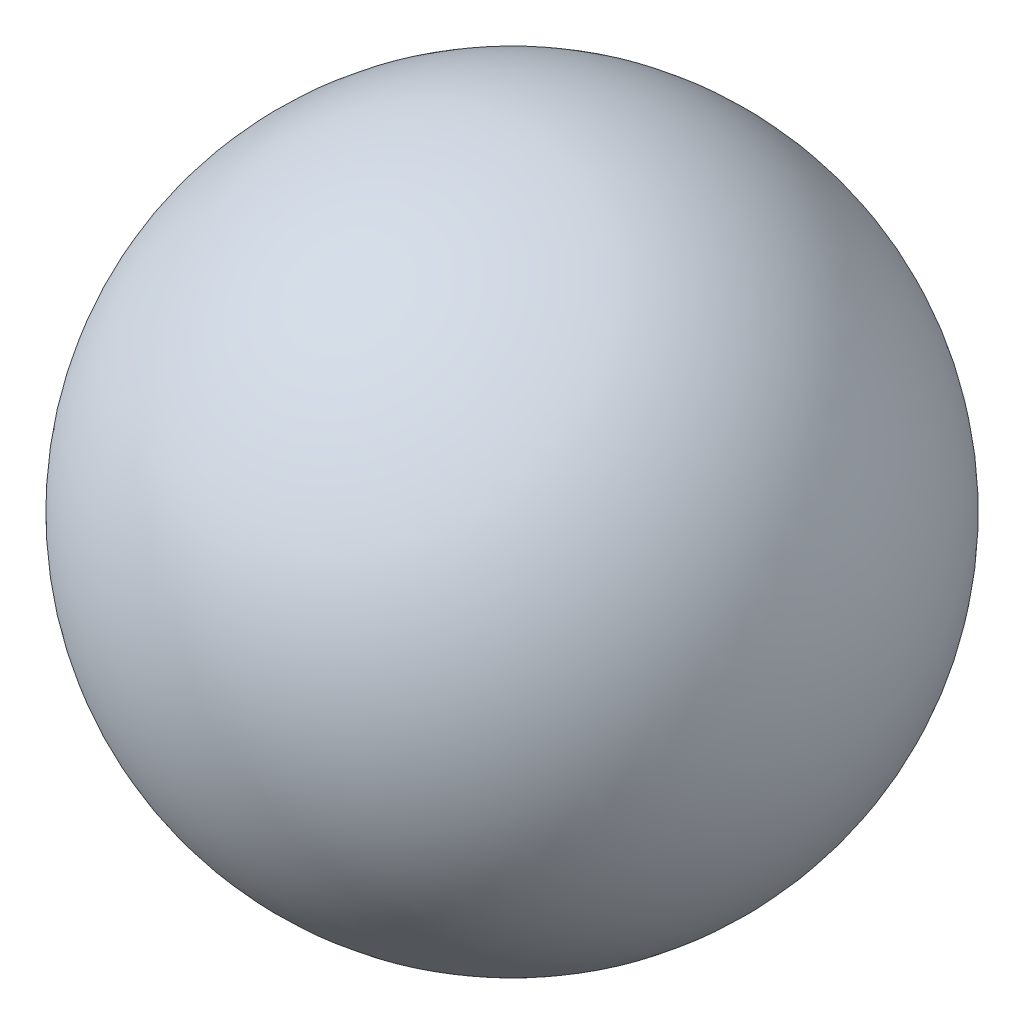
SolidWorks part; units mm, degrees
material "ABS"
ref_plane "Front Plane" through (0, 0, 0) normal (0, 0, 1) x (1, 0, 0)
ref_plane "Top Plane" through (0, 0, 0) normal (0, 1, 0) x (1, 0, 0)
ref_plane "Right Plane" through (0, 0, 0) normal (1, 0, 0) x (0, 0, -1)
sketch "Sketch1" plane through (0, 0, 0) normal (0, 0, 1) x (1, 0, 0)
  line L0 (0, 20) -> (0, 19)
  line L1 (0, -19) -> (0, -20)
  arc A0 (0, 20) -> (0, -20) centre (0, 0) cw
  arc A1 (0, 19) -> (0, -19) centre (0, 0) cw
  dimension "D2" = 19
  dimension "D1" = 40
revolve "Revolve1" add sketch "Sketch1" angle 360 about L0
